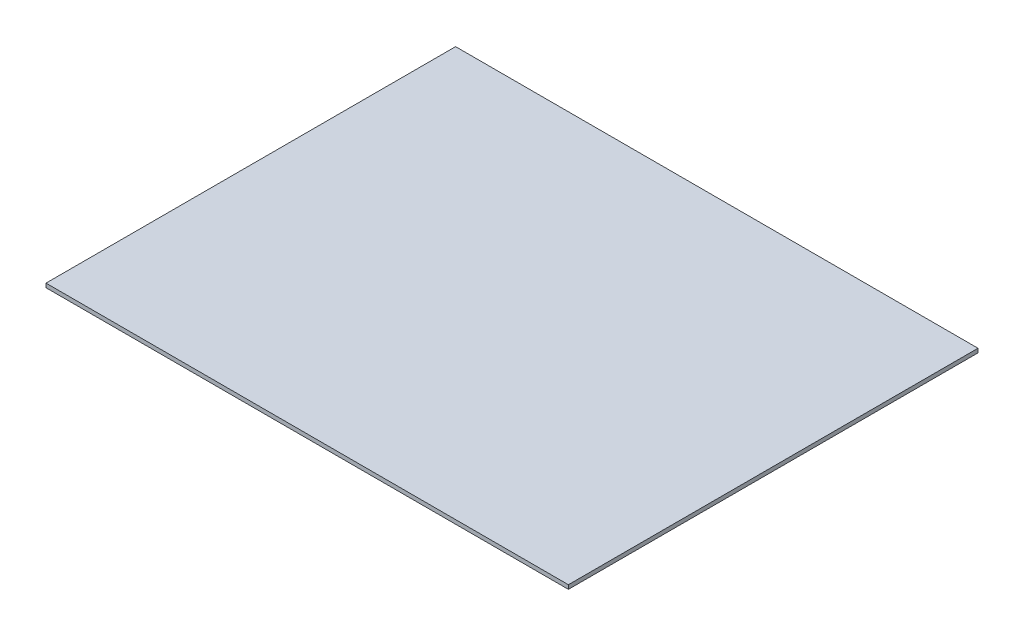
SolidWorks part; units mm, degrees
ref_plane "Front Plane" through (0, 0, 0) normal (0, 0, 1) x (1, 0, 0)
ref_plane "Top Plane" through (0, 0, 0) normal (0, 1, 0) x (1, 0, 0)
ref_plane "Right Plane" through (0, 0, 0) normal (1, 0, 0) x (0, 0, -1)
sketch "Sketch1" plane through (0, 0, 0) normal (0, 1, 0) x (1, 0, 0)
  line L1 (-194.5, 152.5) -> (194.5, 152.5)
  line L2 (-194.5, 152.5) -> (-194.5, -152.5)
  line L3 (-194.5, -152.5) -> (194.5, -152.5)
  line L4 (194.5, 152.5) -> (194.5, -152.5)
  line L5 (-194.5, 152.5) -> (194.5, -152.5) construction
  line L6 (-194.5, -152.5) -> (194.5, 152.5) construction
  point P0 (0, 0)
  dimension "D1" = 305
  dimension "D2" = 389
extrude "Boss-Extrude1" add sketch "Sketch1" along normal blind 3
